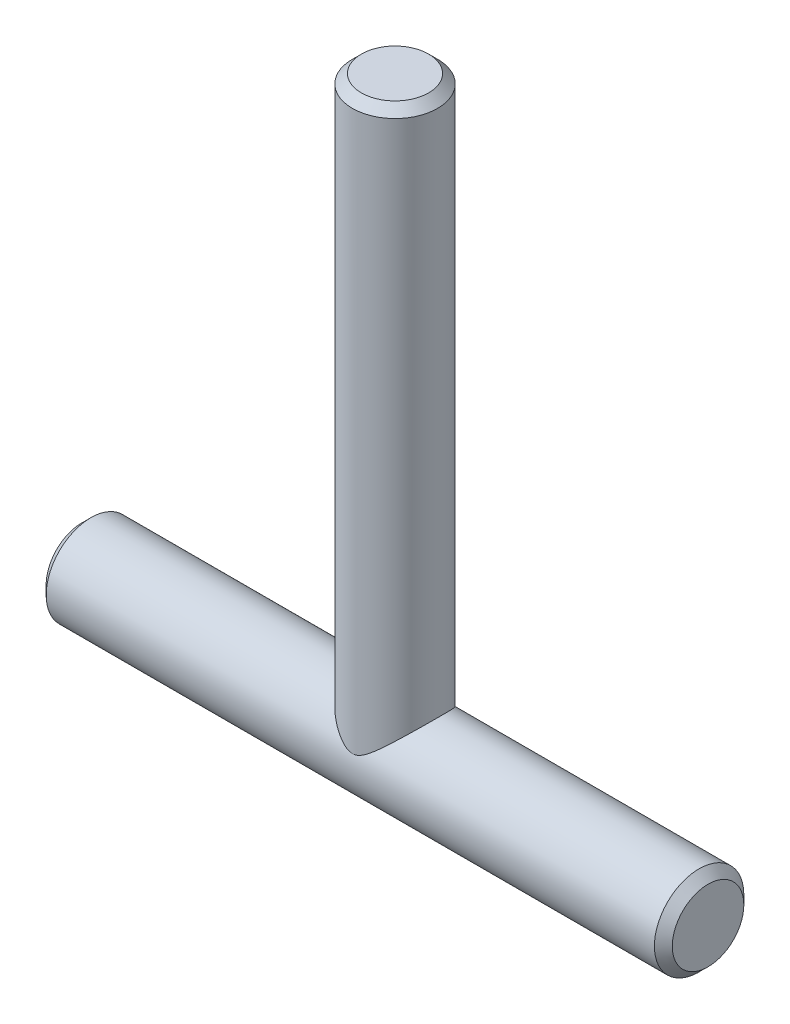
SolidWorks part; units mm, degrees
ref_plane "Front Plane" through (0, 0, 0) normal (0, 0, 1) x (1, 0, 0)
ref_plane "Top Plane" through (0, 0, 0) normal (0, 1, 0) x (1, 0, 0)
ref_plane "Right Plane" through (0, 0, 0) normal (1, 0, 0) x (0, 0, -1)
sketch "Sketch1" plane through (0, 0, 0) normal (1, 0, 0) x (0, 0, -1)
  circle A0 centre (0, -5) radius 5
  point P2 (0, 0)
  dimension "D1" = 10
extrude "Boss-Extrude1" add sketch "Sketch1" along normal mid plane 70
sketch "Sketch2" plane through (0, 0, 0) normal (0, 1, 0) x (1, 0, 0)
  circle A0 centre (0, 0) radius 4.7625
  dimension "D1" = 9.525
extrude "Boss-Extrude5" add sketch "Sketch2" along normal blind 60 and the other way blind 5
cosmetic thread "Cosmetic Thread1" parameters "D1"=50, "D2"=7.6327
chamfer "Chamfer1" distance 1 angle 45 3 edges at (35, -5, -5) (0, 60, 4.7625) (-35, -5, -5)
